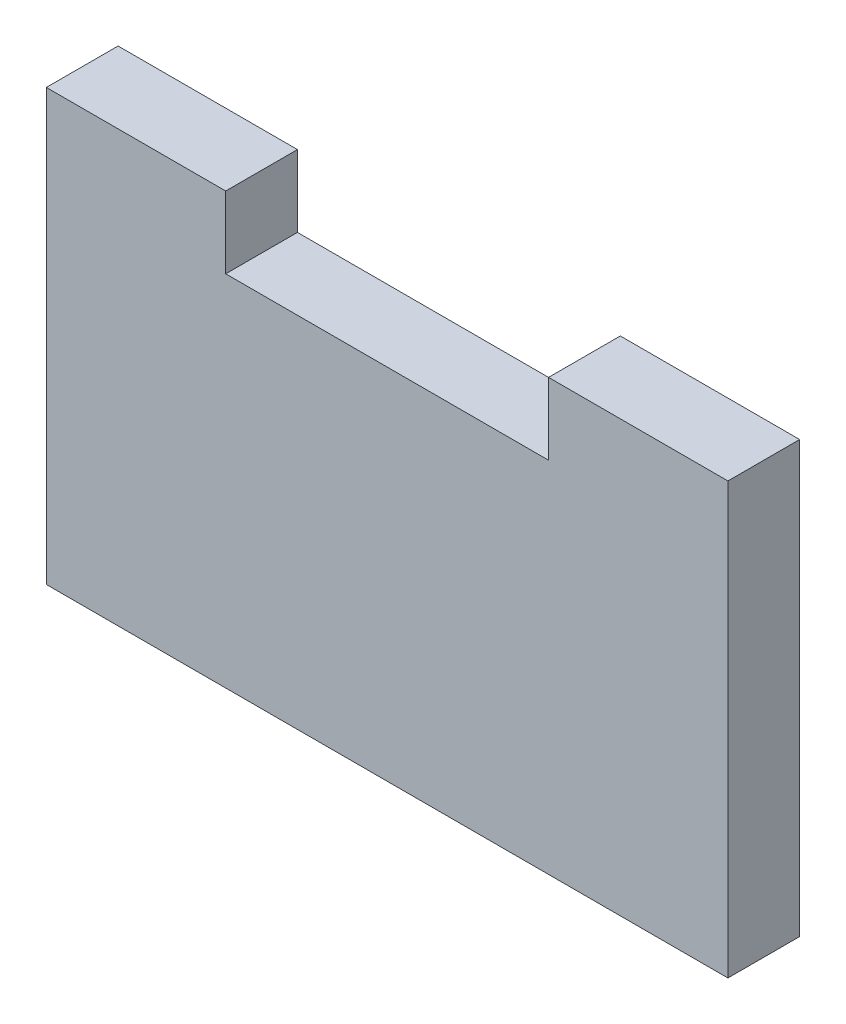
SolidWorks part; units mm, degrees
ref_plane "Front Plane" through (0, 0, 0) normal (0, 0, 1) x (1, 0, 0)
ref_plane "Top Plane" through (0, 0, 0) normal (0, 1, 0) x (1, 0, 0)
ref_plane "Right Plane" through (0, 0, 0) normal (1, 0, 0) x (0, 0, -1)
sketch "Sketch1" plane through (0, 0, 0) normal (0, 0, 1) x (1, 0, 0)
  line L0 (-19, 10) -> (-19, 14)
  line L1 (-19, -10) -> (19, -10)
  line L2 (-19, -10) -> (-19, 10)
  line L3 (-9, 10) -> (9, 10)
  line L4 (19, -10) -> (19, 10)
  line L5 (-19, -10) -> (19, 10) construction
  line L6 (-19, 10) -> (19, -10) construction
  line L7 (-19, 14) -> (-9, 14)
  line L8 (-9, 14) -> (-9, 10)
  line L9 (9, 10) -> (9, 14)
  line L10 (9, 14) -> (19, 14)
  line L11 (19, 14) -> (19, 10)
  point P0 (0, 0)
  point P11 (0, 0)
  dimension "D1" = 20
  dimension "D2" = 38
  dimension "D3" = 10
  dimension "D4" = 4
extrude "Boss-Extrude1" add sketch "Sketch1" along normal blind 4
